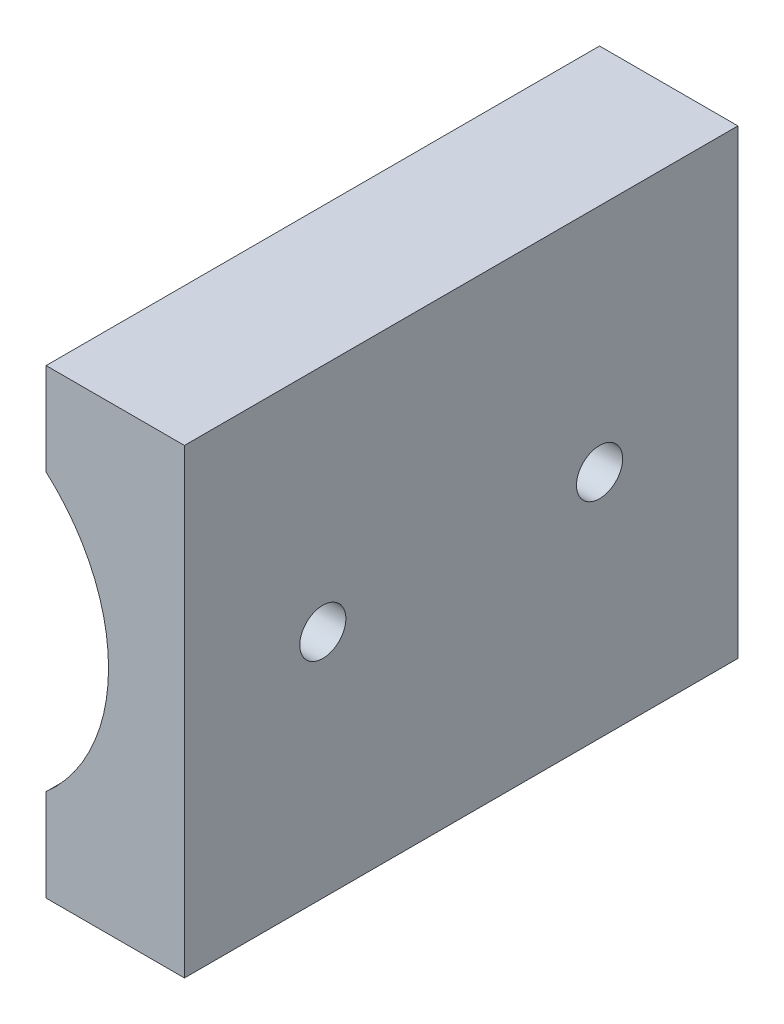
SolidWorks part; units mm, degrees
ref_plane "Front Plane" through (0, 0, 0) normal (0, 0, 1) x (1, 0, 0)
ref_plane "Top Plane" through (0, 0, 0) normal (0, 1, 0) x (1, 0, 0)
ref_plane "Right Plane" through (0, 0, 0) normal (1, 0, 0) x (0, 0, -1)
sketch "Sketch2" plane through (0, 0, 0) normal (0, 0, 1) x (1, 0, 0)
  line L0 (0, 22.4522) -> (0, -27.5478)
  line L1 (0, -27.5478) -> (-15, -27.5478)
  line L2 (-15, -27.5478) -> (-15, -17.5478)
  line L3 (0, 22.4522) -> (-15, 22.4522)
  line L4 (-15, 22.4522) -> (-15, 12.4522)
  arc A0 (-15, 12.4522) -> (-15, -17.5478) centre (-28.2288, -2.5478) cw
  dimension "D2" = 10
  dimension "D1" = 50
  dimension "D3" = 10
  dimension "D4" = 15
  dimension "D5" = 15
extrude "Boss-Extrude1" add sketch "Sketch2" along normal blind 60
sketch "Sketch3" plane through (0, 0, 0) normal (1, 0, 0) x (0, 0, -1)
  line L2 (-30, 22.4522) -> (-30, -27.5478) construction
  line L3 (-60, 22.4522) -> (0, 22.4522) construction
  line L4 (-60, -27.5478) -> (0, -27.5478) construction
  line L5 (-60, -27.5478) -> (-60, 22.4522) construction
  line L6 (-60, -2.5478) -> (0, -2.5478) construction
  line L7 (0, -27.5478) -> (0, 22.4522) construction
  circle A0 centre (-45, -2.5478) radius 2.5
  circle A1 centre (-15, -2.5478) radius 2.5
  dimension "D1" = 5
  dimension "D2" = 5
  dimension "D3" = 15
  dimension "D4" = 15
extrude "Cut-Extrude1" cut sketch "Sketch3" against normal up to next and the other way through all contours A1 | A0
